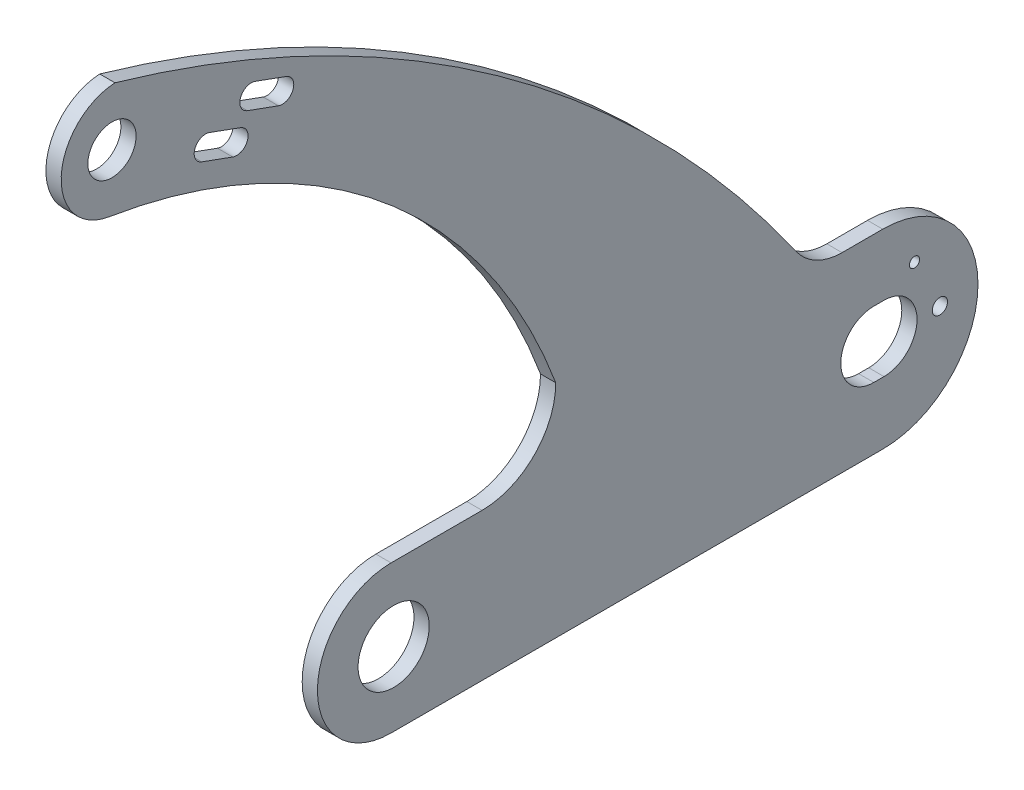
SolidWorks part; units mm, degrees
material "AISI 1020"
ref_plane "Front Plane" through (0, 0, 0) normal (0, 0, 1) x (1, 0, 0)
ref_plane "Top Plane" through (0, 0, 0) normal (0, 1, 0) x (1, 0, 0)
ref_plane "Right Plane" through (0, 0, 0) normal (1, 0, 0) x (0, 0, -1)
sketch "Sketch1" plane through (0, 0, 0) normal (1, 0, 0) x (0, 0, -1)
  line L0 (-48.375, 0) -> (48.375, 0)
  line L1 (48.375, 37.5) -> (40.375, 37.5)
  line L2 (-48.375, 29) -> (-30.475, 29)
  line L3 (0, -31.4761) -> (0, 31.4761) construction
  line L4 (-102.7221, 138) -> (-35.7221, 138) construction
  line L5 (31.3643, 42.1907) -> (-35.7221, 138) construction
  line L6 (46.625, 18.75) -> (48.625, 18.75) construction
  line L9 (-102.7221, 138) -> (-103.8892, 115.7306) construction
  line L10 (-103.3056, 126.8653) -> (-113.2919, 127.3886) construction
  line L11 (-15.975, 43.5) -> (-23.475, 56.4904) construction
  line L12 (58.7209, 18.75) -> (60.4234, 18.75) construction
  line L13 (-50.3822, 14.5) -> (-47.4326, 14.5) construction
  line L14 (-49.1942, 14.5) -> (-46.982, 14.5) construction
  line L15 (-84.8817, 118.0957) -> (-78.7737, 115.8726) construction
  line L16 (-84.1122, 120.21) -> (-78.0042, 117.9869)
  line L17 (-85.6513, 115.9814) -> (-79.5433, 113.7583)
  line L19 (-75.8899, 122.3244) -> (-69.7819, 120.1012) construction
  line L20 (-75.1203, 124.4387) -> (-69.0123, 122.2155)
  line L21 (-76.6594, 120.21) -> (-70.5514, 117.9869)
  line L22 (-78.7737, 117.9869) -> (-78.0042, 117.9869) construction
  line L23 (-70.5514, 117.9869) -> (-69.0123, 117.9869) construction
  line L24 (46.625, 25.25) -> (48.625, 25.25)
  line L25 (46.625, 12.25) -> (48.625, 12.25)
  arc A3 (-48.375, 0) -> (-48.375, 29) centre (-48.375, 14.5) cw
  arc A4 (48.375, 37.5) -> (48.375, 0) centre (48.375, 18.75) cw
  arc A5 (40.375, 37.5) -> (31.3643, 42.1907) centre (40.375, 48.5) cw
  arc A6 (31.3643, 42.1907) -> (-102.7221, 138) centre (-171.3118, -99.7247) ccw
  arc A7 (-15.975, 43.5) -> (-30.475, 29) centre (-30.475, 43.5) cw
  arc A12 (-102.7221, 138) -> (-103.8892, 115.7306) centre (-102.0912, 126.8016) ccw
  arc A13 (-103.8892, 115.7306) -> (-15.975, 43.5) centre (-122.0292, 4.0349) cw
  circle A14 centre (59.625, 18.75) radius 1.5
  circle A17 centre (54.625, 28.75) radius 1
  circle A18 centre (-47.875, 14.5) radius 7
  circle A19 centre (-103.3056, 126.8653) radius 4.75
  arc A20 (-84.1122, 120.21) -> (-85.6513, 115.9814) centre (-84.8817, 118.0957) ccw
  arc A21 (-79.5433, 113.7583) -> (-78.0042, 117.9869) centre (-78.7737, 115.8726) ccw
  arc A22 (-75.1203, 124.4387) -> (-76.6594, 120.21) centre (-75.8899, 122.3244) ccw
  arc A23 (-70.5514, 117.9869) -> (-69.0123, 122.2155) centre (-69.7819, 120.1012) ccw
  arc A24 (48.625, 12.25) -> (48.625, 25.25) centre (48.625, 18.75) ccw
  arc A25 (46.625, 25.25) -> (46.625, 12.25) centre (46.625, 18.75) ccw
  point P14 (0, 0)
  point P26 (47.625, 18.75)
  point P53 (-81.8277, 116.9842)
  point P64 (-72.8359, 121.2128)
  dimension "D4" = 14
  dimension "D3" = 3
  dimension "D1" = 9.5
  dimension "D2" = 2
  dimension "D8" = 247.4218
  dimension "D15" = 46.625
  dimension "D17" = 48.375
  dimension "D18" = 15.975
  dimension "D11" = 2.25
  dimension "D16" = 47.625
  dimension "D21" = 35.7221
  dimension "D24" = 69.7819
  dimension "D26" = 78.0042
  dimension "D19" = 54.625
  dimension "D5" = 14.5
  dimension "D6" = 18.75
  dimension "D7" = 11
  dimension "D9" = 11.2161
  dimension "D10" = 113.1591
  dimension "D12" = 6.5
  dimension "D13" = 31.3643
  dimension "D14" = 40.375
  dimension "D20" = 59.625
  dimension "D22" = 69.0123
  dimension "D23" = 47.875
  dimension "D25" = 72.8359
  dimension "D27" = 102.0912
  dimension "D28" = 103.3056
  dimension "D29" = 28.75
  dimension "D30" = 25.2512
  dimension "D31" = 113.7583
  dimension "D32" = 0.4506
  dimension "D33" = 2.9496
  dimension "D34" = 2.0072
  dimension "D35" = 2.2122
  dimension "D36" = 62.9523
  dimension "D37" = 10.0959
  dimension "D38" = 13.7984
  dimension "D39" = 6.5
  dimension "D40" = 15
  dimension "D41" = 56.4904
extrude "Boss-Extrude1" add sketch "Sketch1" along normal blind 3
sketch "Sketch2" plane through (3, 0, 0) normal (1, 0, 0) x (0, 0, -1)
  line L0 (47.625, 25.25) -> (47.625, 12.25) construction
  line L1 (48.625, 25.25) -> (46.625, 25.25) construction
  line L2 (46.625, 12.25) -> (48.625, 12.25) construction
  circle A0 centre (47.625, 18.75) radius 8.7923 construction
  dimension "D1" = 17.5846
